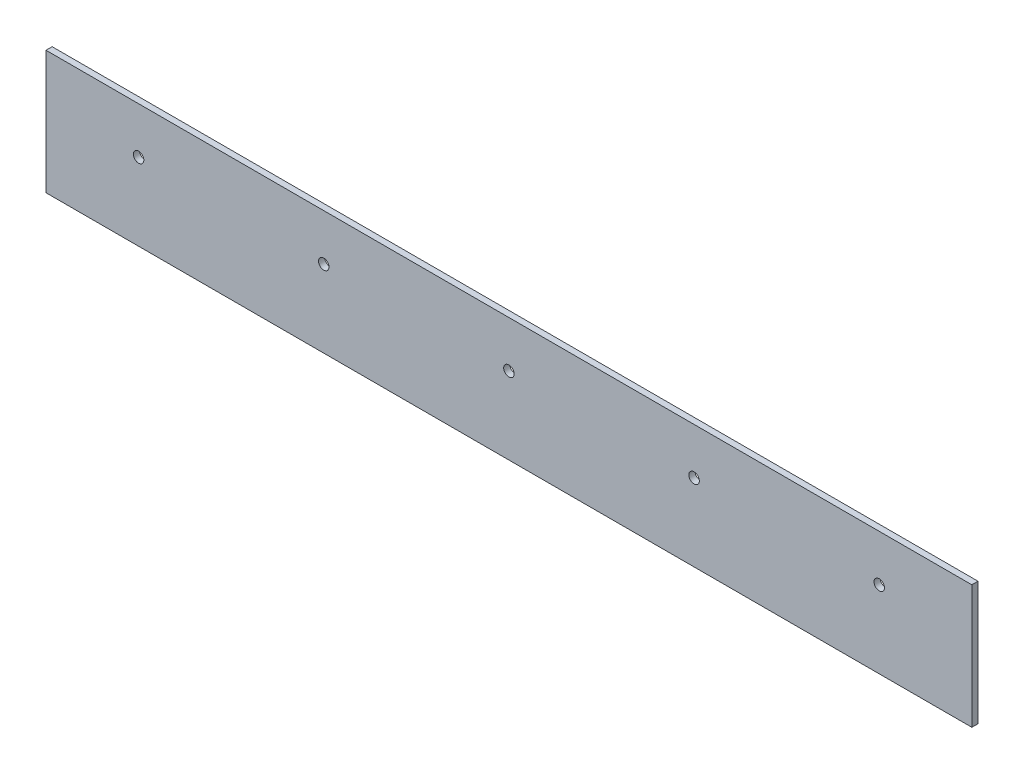
SolidWorks part; units mm, degrees
ref_plane "Front Plane" through (0, 0, 0) normal (0, 0, 1) x (1, 0, 0)
ref_plane "Top Plane" through (0, 0, 0) normal (0, 1, 0) x (1, 0, 0)
ref_plane "Right Plane" through (0, 0, 0) normal (1, 0, 0) x (0, 0, -1)
sketch "Sketch1" plane through (0, 0, 0) normal (0, 0, 1) x (1, 0, 0)
  line L1 (0, 0) -> (1500, 0)
  line L2 (0, 0) -> (0, 200)
  line L3 (0, 200) -> (1500, 200)
  line L4 (1500, 0) -> (1500, 200)
  circle A0 centre (150, 125) radius 8.5
  circle A5 centre (450, 125) radius 8.5
  circle A6 centre (750, 125) radius 8.5
  circle A7 centre (1050, 125) radius 8.5
  circle A8 centre (1350, 125) radius 8.5
  point P8 (0, 0)
  dimension "D3" = 17
  dimension "D1" = 1500
  dimension "D2" = 200
  dimension "D4" = 150
  dimension "D6" = 75
  dimension "D5" = 5
extrude "Boss-Extrude1" add sketch "Sketch1" along normal blind 10
